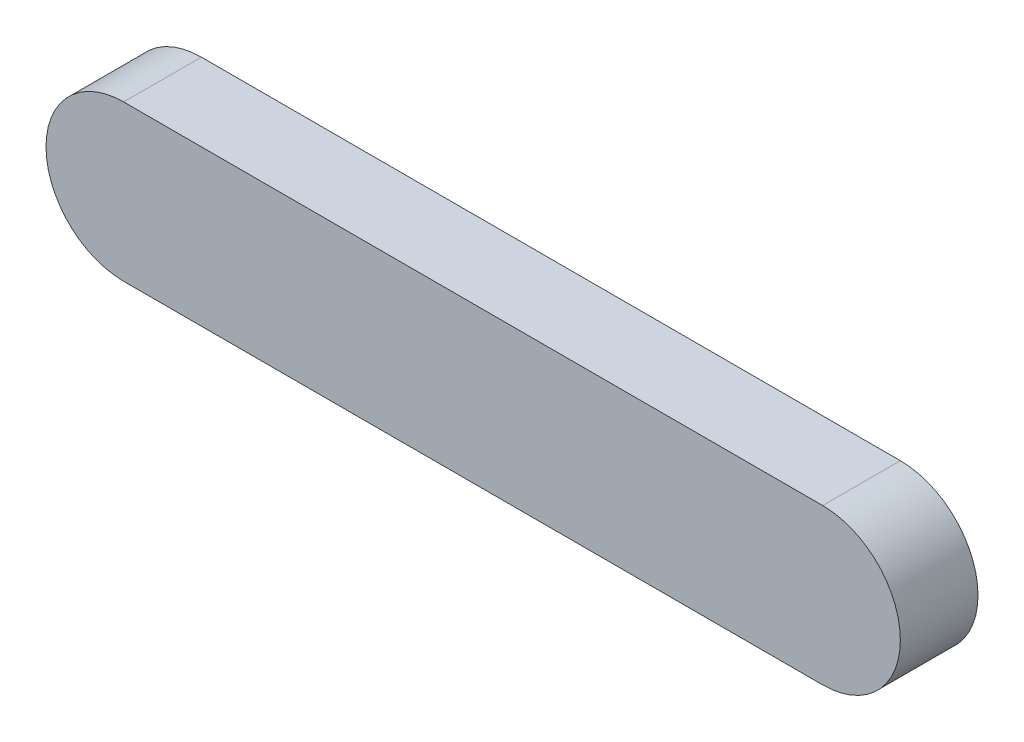
SolidWorks part; units mm, degrees
ref_plane "Front Plane" through (0, 0, 0) normal (0, 0, 1) x (1, 0, 0)
ref_plane "Top Plane" through (0, 0, 0) normal (0, 1, 0) x (1, 0, 0)
ref_plane "Right Plane" through (0, 0, 0) normal (1, 0, 0) x (0, 0, -1)
sketch "Sketch1" plane through (0, 0, 0) normal (0, 0, 1) x (1, 0, 0)
  line L1 (0, 0) -> (114.3, 0)
  line L3 (0, -25.4) -> (114.3, -25.4)
  arc A0 (0, -25.4) -> (0, 0) centre (0, -12.7) cw
  arc A1 (114.3, 0) -> (114.3, -25.4) centre (114.3, -12.7) cw
  dimension "D1" = 114.3
  dimension "D2" = 12.7
  dimension "D3" = 12.7
  dimension "D4" = 25.4
extrude "Boss-Extrude1" add sketch "Sketch1" against normal blind 12.7
sketch "Sketch2" plane through (0, 0, -12.7) normal (0, 0, -1) x (-1, 0, 0)
  line L0 (0, 0) -> (0, -25.4) construction
  line L1 (-118.8726, -12.7) -> (-117.4756, -12.7) construction
  line L2 (-118.8726, -11.6205) -> (-118.8726, -13.7795)
  line L3 (-117.4756, -12.7) -> (-118.8726, -12.7) construction
  line L4 (-118.8726, -11.6205) -> (-117.2859, -11.6205)
  line L5 (-118.8726, -13.7795) -> (-117.2859, -13.7795)
  line L6 (-111.125, -12.7) -> (12.7, -12.7) construction
  line L7 (-109.7274, -13.7795) -> (-111.3141, -13.7795)
  line L8 (-109.7274, -13.7795) -> (-109.7274, -11.6205)
  line L9 (-109.7274, -11.6205) -> (-111.3141, -11.6205)
  line L10 (-57.15, 0) -> (-57.15, -25.4) construction
  line L11 (-114.3, 0) -> (0, 0) construction
  line L12 (0, -25.4) -> (-114.3, -25.4) construction
  line L13 (-4.5726, -11.6205) -> (-2.9859, -11.6205)
  line L14 (-4.5726, -13.7795) -> (-4.5726, -11.6205)
  line L15 (-4.5726, -13.7795) -> (-2.9859, -13.7795)
  line L16 (4.5726, -13.7795) -> (2.9859, -13.7795)
  line L17 (4.5726, -11.6205) -> (4.5726, -13.7795)
  line L18 (4.5726, -11.6205) -> (2.9859, -11.6205)
  arc A0 (-117.2859, -13.7795) -> (-111.3141, -13.7795) centre (-114.3, -12.7) ccw
  arc A1 (-2.9859, -13.7795) -> (2.9859, -13.7795) centre (0, -12.7) ccw
  arc A3 (0, -25.4) -> (0, 0) centre (0, -12.7) ccw construction
  arc A4 (2.9859, -11.6205) -> (-2.9859, -11.6205) centre (0, -12.7) ccw
  arc A5 (-111.3141, -11.6205) -> (-117.2859, -11.6205) centre (-114.3, -12.7) ccw
  arc A6 (-117.2859, -13.7795) -> (-111.3141, -13.7795) centre (-114.3, -12.7) ccw
  arc A7 (-111.3141, -11.6205) -> (-117.2859, -11.6205) centre (-114.3, -12.7) ccw
  point P18 (-118.8726, -12.7)
  point P30 (-114.3, -12.7)
  dimension "D2" = 6.35
  dimension "D3" = 2.159
  dimension "D4" = 1.397
  dimension "D5" = 2
extrude "Cut-Extrude1" cut sketch "Sketch2" against normal blind 6.35 contours A0 L4 L2 L5 | L18 A4 L13 L14 L15 A1 L16 L17
sketch "Sketch3" plane through (0, 0, -6.35) normal (0, 0, -1) x (-1, 0, 0)
  line L0 (-118.8726, -11.6205) -> (-117.2859, -11.6205) construction
  line L1 (-57.15, 0) -> (-57.15, -25.4) construction
  line L2 (-118.8726, -11.6205) -> (-117.2859, -11.6205)
  line L3 (1.0795, -15.6859) -> (1.0795, -17.2726)
  line L4 (-2.9859, -13.7795) -> (-4.5726, -13.7795)
  line L5 (-1.0795, -8.1274) -> (-1.0795, -9.7141)
  line L6 (4.5726, -11.6205) -> (2.9859, -11.6205)
  line L7 (-114.3, 0) -> (0, 0) construction
  line L8 (0, -25.4) -> (-114.3, -25.4) construction
  line L10 (-113.2205, -8.1274) -> (-113.2205, -9.7141)
  line L12 (-111.3141, -13.7795) -> (-109.7274, -13.7795)
  line L13 (-115.3795, -15.6859) -> (-115.3795, -17.2726)
  arc A0 (-115.3795, -17.2726) -> (-109.7274, -13.7795) centre (-114.3, -12.7) ccw
  arc A1 (-117.2859, -13.7795) -> (-111.3141, -13.7795) centre (-114.3, -12.7) ccw construction
  arc A2 (1.0795, -15.6859) -> (-2.9859, -13.7795) centre (0, -12.7) cw
  arc A3 (-1.0795, -9.7141) -> (2.9859, -11.6205) centre (0, -12.7) cw
  arc A4 (-1.0795, -8.1274) -> (4.5726, -11.6205) centre (0, -12.7) cw
  arc A5 (-115.3795, -17.2726) -> (-109.7274, -13.7795) centre (-114.3, -12.7) ccw
  arc A6 (-113.2205, -8.1274) -> (-118.8726, -11.6205) centre (-114.3, -12.7) ccw
  arc A7 (-111.3141, -11.6205) -> (-117.2859, -11.6205) centre (-114.3, -12.7) ccw construction
  arc A8 (-113.2205, -9.7141) -> (-117.2859, -11.6205) centre (-114.3, -12.7) ccw
  arc A9 (-115.3795, -15.6859) -> (-111.3141, -13.7795) centre (-114.3, -12.7) ccw
  arc A10 (1.0795, -17.2726) -> (-4.5726, -13.7795) centre (0, -12.7) cw
  arc A11 (1.0795, -17.2726) -> (-4.5726, -13.7795) centre (0, -12.7) cw
  point P35 (-114.3, -12.7)
  arc M4 (-111.3141, -11.6205) -> (-117.2859, -11.6205) centre (-114.3, -12.7) ccw
  line M5 (-117.2859, -11.6205) -> (-118.8726, -11.6205)
  arc M8 (-117.2859, -13.7795) -> (-111.3141, -13.7795) centre (-114.3, -12.7) ccw
  line M9 (-111.3141, -13.7795) -> (-109.7274, -13.7795)
extrude "Cut-Extrude4" cut sketch "Sketch3" along normal blind 3.81 contours L10 A6 M5 M4 | L13 A0 M9 M8 | A4 L5 A3 L6 | A10 L3 A2 L4
sketch "Sketch4" plane through (0, 0, -6.35) normal (0, 0, -1) x (-1, 0, 0)
  line L18 (-113.2205, -8.1274) -> (-113.2205, -9.7141)
  line L19 (-113.2205, -8.1274) -> (-115.3795, -8.1274)
  line L20 (-115.3795, -8.1274) -> (-115.3795, -9.7141)
  line L24 (-115.3795, -17.2726) -> (-115.3795, -15.6859)
  line L25 (-115.3795, -17.2726) -> (-113.2205, -17.2726)
  line L26 (-113.2205, -17.2726) -> (-113.2205, -15.6859)
  arc A0 (-115.3795, -15.6859) -> (-113.2205, -15.6859) centre (-114.3, -12.7) ccw
  arc A1 (-114.8117, -9.5665) -> (-115.3795, -9.7141) centre (-114.3, -12.7) ccw
  arc A2 (-111.3141, -11.6205) -> (-113.2205, -9.7141) centre (-114.3, -12.7) ccw construction
  arc A3 (-113.2205, -9.7141) -> (-115.3795, -9.7141) centre (-114.3, -12.7) ccw
  point P31 (-114.3, -12.7)
  line M43 (-113.2205, -9.7141) -> (-113.2205, -8.1274)
  line M45 (-115.3795, -15.6859) -> (-115.3795, -17.2726)
ref_plane "Plane1" through (57.15, 0, 0) normal (1, 0, 0) x (0, 0, -1)
extrude "Cut-Extrude5" cut sketch "Sketch4" along normal blind 5.08 contours A3 L19 L20 A1 M43 | A0 L25 L26 M45
mirror "Mirror2" about plane through (57.15, 0, 0) normal (1, 0, 0) of "Cut-Extrude5"
